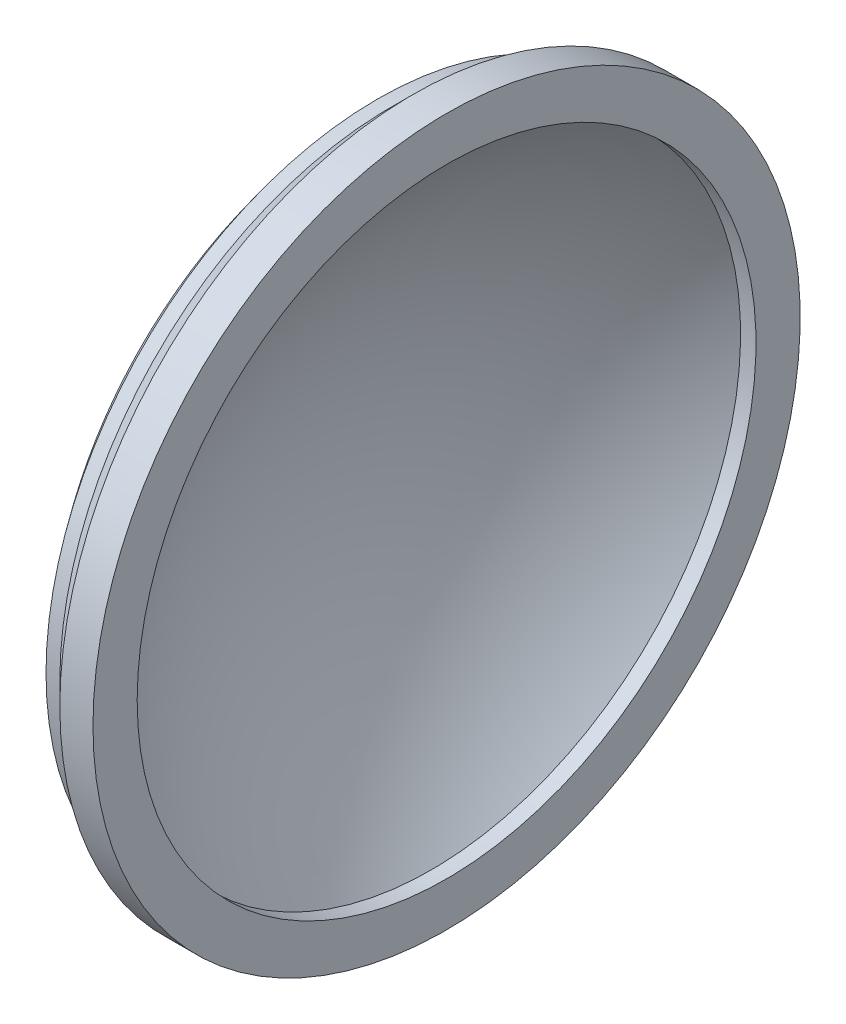
SolidWorks part; units mm, degrees
ref_plane "Front Plane" through (0, 0, 0) normal (0, 0, 1) x (1, 0, 0)
ref_plane "Top Plane" through (0, 0, 0) normal (0, 1, 0) x (1, 0, 0)
ref_plane "Right Plane" through (0, 0, 0) normal (1, 0, 0) x (0, 0, -1)
sketch "Sketch1" plane through (0, 0, 0) normal (0, 0, 1) x (1, 0, 0)
  line L0 (-95.2866, 0) -> (130.5844, 0) construction
  line L1 (-28.5, 60) -> (-26, 60)
  line L2 (-26, 60) -> (-22, 64)
  line L3 (-22, 64) -> (-16, 64)
  line L4 (-16, 64) -> (-16, 56)
  line L5 (-16, 56) -> (-18.7907, 56)
  line L6 (-49.8454, 0) -> (-39.8454, 0)
  arc A0 (-18.7907, 56) -> (-39.8454, 0) centre (45.1546, 0) ccw
  arc A1 (-28.5, 60) -> (-49.8454, 0) centre (45.1546, 0) ccw
  dimension "D3" = 95
  dimension "D4" = 85
  dimension "D1" = 64
  dimension "D2" = 16
  dimension "D5" = 2.5
  dimension "D6" = 4
  dimension "D7" = 8
  dimension "D8" = 6
  dimension "D9" = 135
revolve "Revolve1" add sketch "Sketch1" angle 360 about L0
